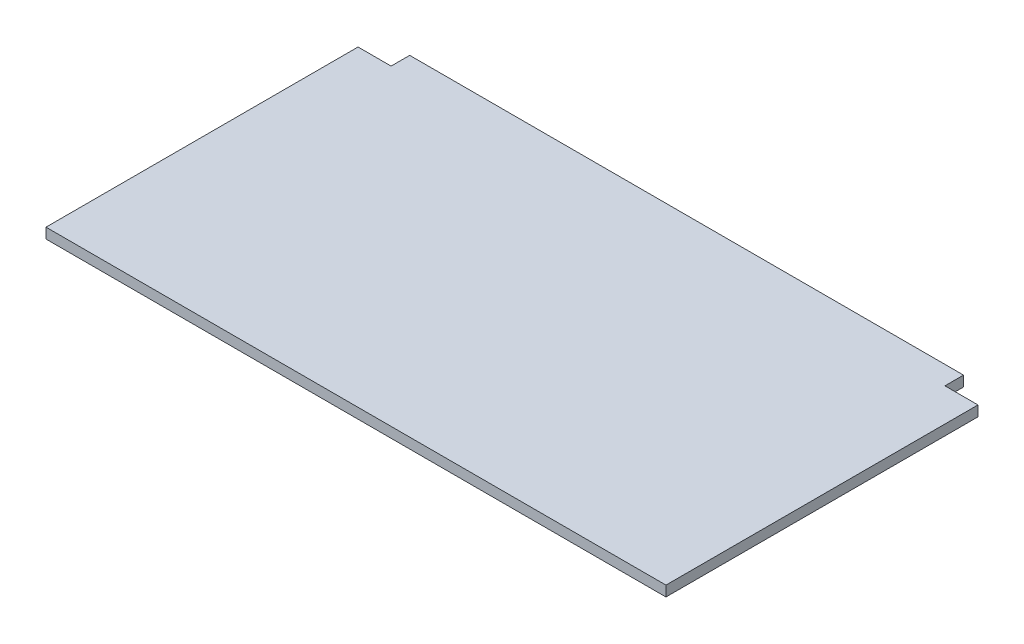
SolidWorks part; units mm, degrees
material "Cedar"
ref_plane "Front Plane" through (0, 0, 0) normal (0, 0, 1) x (1, 0, 0)
ref_plane "Top Plane" through (0, 0, 0) normal (0, 1, 0) x (1, 0, 0)
ref_plane "Right Plane" through (0, 0, 0) normal (1, 0, 0) x (0, 0, -1)
sketch "Sketch1" plane through (0, 0, 0) normal (0, 1, 0) x (1, 0, 0)
  line L1 (750, -400) -> (-750, -400)
  line L2 (750, -400) -> (750, 400)
  line L3 (750, 400) -> (-750, 400)
  line L4 (-750, -400) -> (-750, 400)
  line L5 (750, -400) -> (-750, 400) construction
  line L6 (750, 400) -> (-750, -400) construction
  point P0 (0, 0)
  dimension "D1" = 800
  dimension "D2" = 1500
extrude "RawMaterial" add sketch "Sketch1" along normal blind 25
sketch "Sketch2" plane through (0, 25, 0) normal (0, 1, 0) x (1, 0, 0)
  line L0 (750, 400) -> (-750, 400) construction
  line L1 (-761.4719, 422.6992) -> (-670, 422.6992)
  line L2 (-761.4719, 422.6992) -> (-761.4719, 355)
  line L3 (-761.4719, 355) -> (-670, 355)
  line L4 (-670, 422.6992) -> (-670, 355)
  line L5 (777.3454, 416.3957) -> (670, 416.3957)
  line L6 (777.3454, 416.3957) -> (777.3454, 355)
  line L7 (777.3454, 355) -> (670, 355)
  line L8 (670, 416.3957) -> (670, 355)
  line L9 (-750, 400) -> (-750, -400) construction
  line L10 (750, -400) -> (750, 400) construction
  line M5 (-750, 400) -> (-750, -400)
  line M7 (750, -400) -> (750, 400)
  line M8 (750, 400) -> (-750, 400)
  dimension "D1" = 45
  dimension "D2" = 80
  dimension "D3" = 80
extrude "SlotsForFrame" cut sketch "Sketch2" against normal through all contours L4 L3 M8 M5 | L8 L7 M8 M7
equation "\"D3@Sketch2\"=\"D2@Sketch2\""
equation "\"TableThickness\"= \"Thickness@RawMaterial\""
